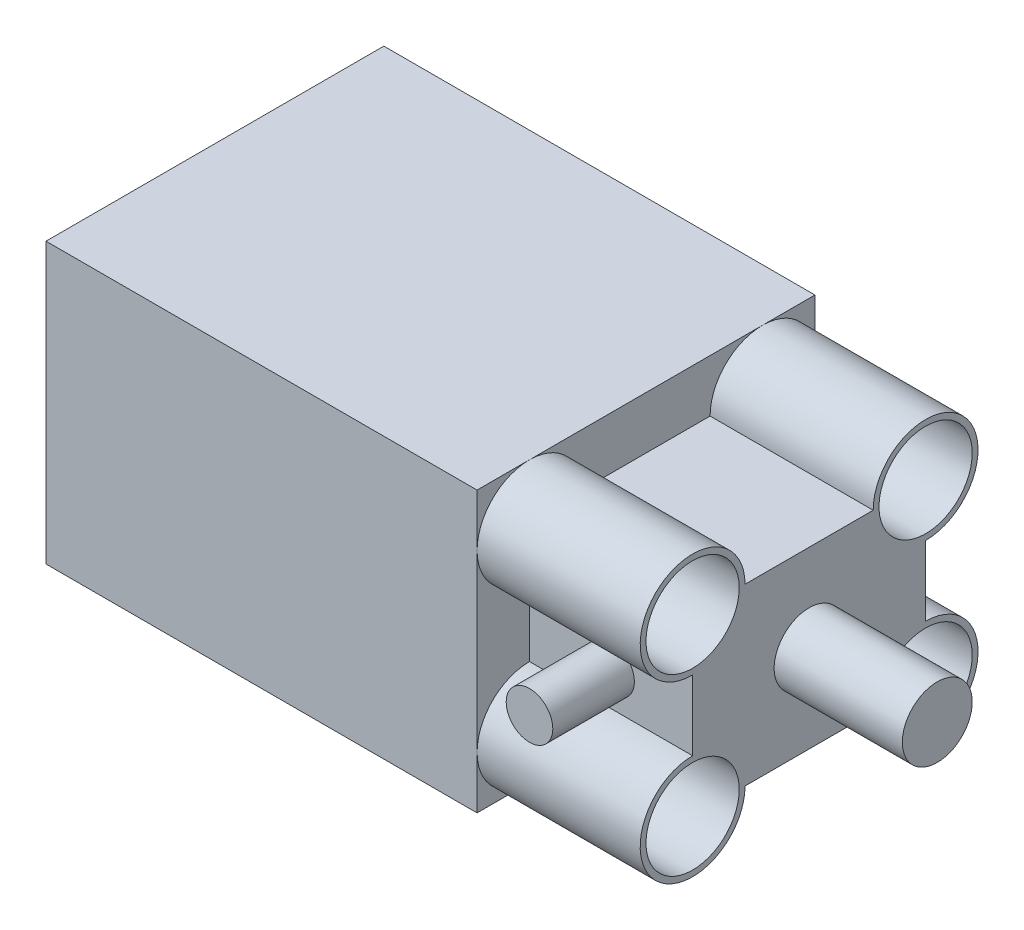
SolidWorks part; units mm, degrees
ref_plane "정면도" through (0, 0, 0) normal (0, 0, 1) x (1, 0, 0)
ref_plane "평면도" through (0, 0, 0) normal (0, 1, 0) x (1, 0, 0)
ref_plane "우측면도" through (0, 0, 0) normal (1, 0, 0) x (0, 0, -1)
sketch "스케치1" plane through (0, 0, 0) normal (0, 1, 0) x (1, 0, 0)
  line L1 (9.25, 7.25) -> (-9.25, 7.25)
  line L2 (9.25, 7.25) -> (9.25, -7.25)
  line L3 (9.25, -7.25) -> (-9.25, -7.25)
  line L4 (-9.25, 7.25) -> (-9.25, -7.25)
  line L5 (0, -7.25) -> (0, 7.25) construction
  line L6 (9.25, 0) -> (-9.25, 0) construction
  point P0 (0, 0)
  dimension "D1" = 18.5
  dimension "D2" = 14.5
extrude "보스-돌출1" add sketch "스케치1" along normal blind 12
sketch "스케치2" plane through (9.25, 0, 0) normal (1, 0, 0) x (0, 0, -1)
  line L0 (-7.25, 12) -> (7.25, 12) construction
  line L1 (-7.25, 12) -> (-7.25, 0) construction
  line L2 (-7.25, 0) -> (7.25, 0) construction
  line L3 (7.25, 12) -> (7.25, 0) construction
  line L4 (-2.75, 9.75) -> (2.75, 9.75)
  line L5 (5, 7.5) -> (5, 4.5)
  line L6 (2.75, 2.25) -> (-2.75, 2.25)
  line L7 (-5, 7.5) -> (-5, 4.5)
  circle A0 centre (5, 9.75) radius 2.25
  circle A1 centre (5, 2.25) radius 2.25
  circle A2 centre (-5, 2.25) radius 2.25
  circle A3 centre (-5, 9.75) radius 2.25
  circle A4 centre (-5, 9.75) radius 2
  circle A5 centre (5, 9.75) radius 2
  circle A6 centre (5, 2.25) radius 2
  circle A7 centre (-5, 2.25) radius 2
  dimension "D1" = 4.5
  dimension "D2" = 4.5
  dimension "D3" = 4.5
  dimension "D4" = 4.5
  dimension "D5" = 4
extrude "보스-돌출2" add sketch "스케치2" along normal blind 7 contours A3 A4 | A3 L7 A2 L6 A1 L5 A0 L4 | A0 A5 | A1 A6 | A2 A7
sketch "스케치4" plane through (16.25, 0, 0) normal (1, 0, 0) x (0, 0, -1)
  line L0 (-7.25, 12) -> (7.25, 0) construction
  line L1 (-7.25, 0) -> (7.25, 12) construction
  line L4 (-7.25, 0) -> (7.25, 0)
  line L5 (-7.25, 12) -> (-7.25, 0)
  line L6 (7.25, 12) -> (-7.25, 12)
  line L7 (7.25, 0) -> (7.25, 12)
  line L8 (-7.25, 0) -> (7.25, 0) construction
  line L9 (-7.25, 12) -> (-7.25, 0) construction
  line L10 (7.25, 12) -> (-7.25, 12) construction
  line L11 (7.25, 0) -> (7.25, 12) construction
  circle A0 centre (0, 6) radius 1.5
  point P2 (0, 0)
  point P6 (0, 6)
  point P8 (0, 0)
  dimension "D1" = 3
  dimension "D2" = 0
extrude "보스-돌출3" add sketch "스케치4" along normal blind 5.5
sketch "스케치6" plane through (0, 0, 5) normal (0, 0, 1) x (1, 0, 0)
  line L0 (9.25, 7.5) -> (16.25, 4.5) construction
  line L1 (9.25, 4.5) -> (16.25, 7.5) construction
  line L4 (9.25, 7.5) -> (9.25, 4.5)
  line L5 (9.25, 4.5) -> (16.25, 4.5)
  line L6 (16.25, 4.5) -> (16.25, 7.5)
  line L7 (16.25, 7.5) -> (9.25, 7.5)
  line L8 (9.25, 7.5) -> (9.25, 4.5) construction
  line L9 (9.25, 4.5) -> (16.25, 4.5) construction
  line L10 (16.25, 4.5) -> (16.25, 7.5) construction
  line L11 (16.25, 7.5) -> (9.25, 7.5) construction
  circle A0 centre (12.75, 6) radius 1
  dimension "D2" = 2
  dimension "D1" = 0
extrude "보스-돌출4" add sketch "스케치6" along normal blind 3.5
